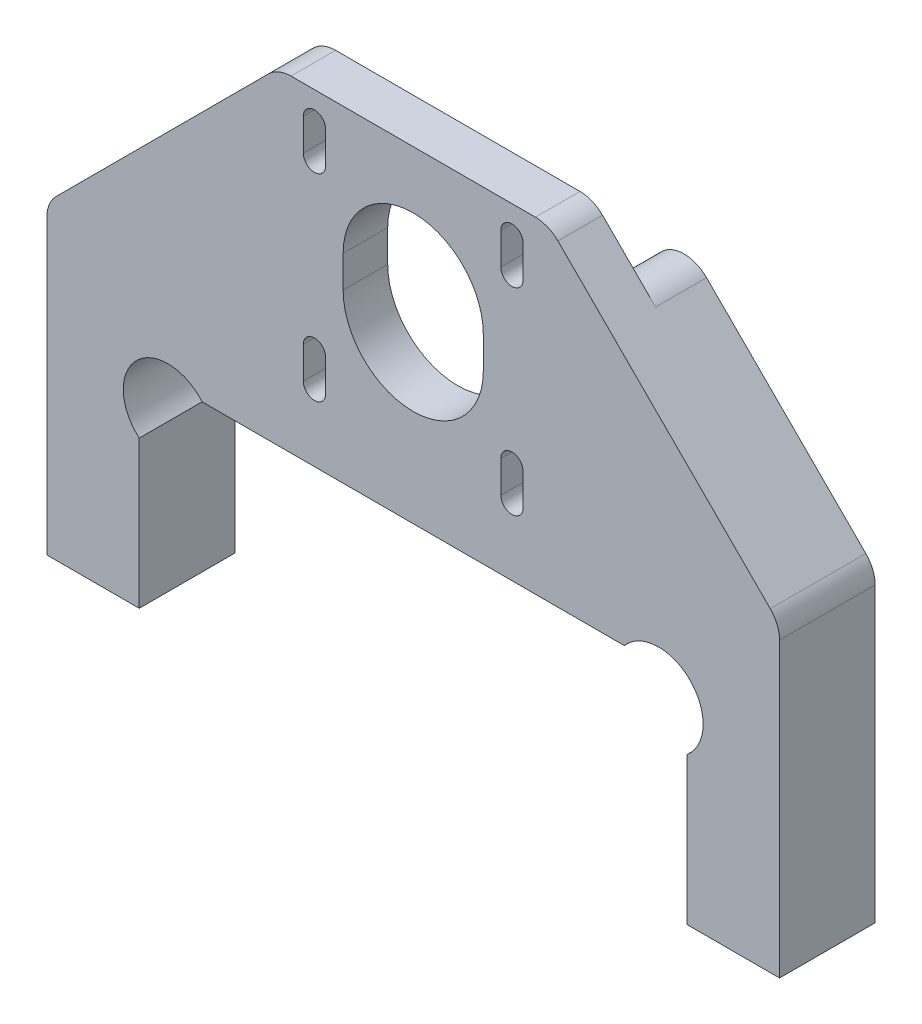
SolidWorks part; units mm, degrees
ref_plane "Ebene vorne" through (0, 0, 0) normal (0, 0, 1) x (1, 0, 0)
ref_plane "Ebene oben" through (0, 0, 0) normal (0, 1, 0) x (1, 0, 0)
ref_plane "Ebene rechts" through (0, 0, 0) normal (1, 0, 0) x (0, 0, -1)
sketch "Skizze1" plane through (0, 0, 0) normal (0, 0, 1) x (1, 0, 0)
  line L0 (100.5, 0) -> (115, 0)
  line L1 (0, 0) -> (14.5, 0)
  line L2 (0, 0) -> (0, 48)
  line L4 (115, 0) -> (115, 48)
  line L5 (0, 48) -> (36.25, 84.25)
  line L6 (14.5, 0) -> (14.5, 23.1381)
  line L7 (24.3619, 33) -> (90.6381, 33)
  line L8 (100.5, 0) -> (100.5, 23.1381)
  line L9 (36.25, 84.25) -> (78.75, 84.25)
  line L10 (78.75, 84.25) -> (115, 48)
  line L11 (57.5, 64.25) -> (57.5, 59.25) construction
  line L12 (68.5, 64.25) -> (68.5, 59.25)
  line L13 (46.5, 64.25) -> (46.5, 59.25)
  line L14 (42, 79.75) -> (42, 74.75) construction
  line L15 (43.75, 79.75) -> (43.75, 74.75)
  line L16 (40.25, 79.75) -> (40.25, 74.75)
  line L17 (73, 79.75) -> (73, 74.75) construction
  line L18 (74.75, 79.75) -> (74.75, 74.75)
  line L19 (71.25, 79.75) -> (71.25, 74.75)
  line L20 (73, 48.75) -> (73, 43.75) construction
  line L21 (74.75, 48.75) -> (74.75, 43.75)
  line L22 (71.25, 48.75) -> (71.25, 43.75)
  line L23 (42, 48.75) -> (42, 43.75) construction
  line L24 (43.75, 48.75) -> (43.75, 43.75)
  line L25 (40.25, 48.75) -> (40.25, 43.75)
  arc A0 (68.5, 64.25) -> (46.5, 64.25) centre (57.5, 64.25) ccw
  arc A1 (46.5, 59.25) -> (68.5, 59.25) centre (57.5, 59.25) ccw
  arc A2 (43.75, 79.75) -> (40.25, 79.75) centre (42, 79.75) ccw
  arc A3 (40.25, 74.75) -> (43.75, 74.75) centre (42, 74.75) ccw
  arc A4 (74.75, 79.75) -> (71.25, 79.75) centre (73, 79.75) ccw
  arc A5 (71.25, 74.75) -> (74.75, 74.75) centre (73, 74.75) ccw
  arc A6 (74.75, 48.75) -> (71.25, 48.75) centre (73, 48.75) ccw
  arc A7 (71.25, 43.75) -> (74.75, 43.75) centre (73, 43.75) ccw
  arc A8 (43.75, 48.75) -> (40.25, 48.75) centre (42, 48.75) ccw
  arc A9 (40.25, 43.75) -> (43.75, 43.75) centre (42, 43.75) ccw
  arc A10 (24.3619, 33) -> (14.5, 23.1381) centre (19, 28.5) ccw
  arc A11 (100.5, 23.1381) -> (90.6381, 33) centre (96, 28.5) ccw
  point P11 (57.5, 61.75)
  point P20 (42, 77.25)
  point P30 (73, 77.25)
  point P37 (73, 46.25)
  point P44 (42, 46.25)
  dimension "D7" = 61.75
  dimension "D20" = 14
  dimension "D21" = 14
  dimension "D23" = 4.5
  dimension "D24" = 4.5
  dimension "D3" = 42.5
  dimension "D4" = 14.5
  dimension "D5" = 115
  dimension "D6" = 36.25
  dimension "D8" = 45
  dimension "D9" = 45
  dimension "D10" = 22
  dimension "D11" = 5
  dimension "D12" = 22.5
  dimension "D13" = 21.25
  dimension "D14" = 3.5
  dimension "D15" = 5
  dimension "D16" = 15.5
  dimension "D17" = 15.5
  dimension "D22" = 4.5
  dimension "D25" = 4.5
  dimension "D18" = 2
  dimension "D19" = 2
extrude "Aufsatz-Linear austragen1" add sketch "Skizze1" along normal blind 15
hole_wizard "M5 Gewindebohrung1" positions "Skizze3" profile "Skizze2" tap size "M5" standard "DIN"
sketch "Skizze3" plane through (0, 0, 0) normal (0, -1, 0) x (-1, 0, 0)
  line L0 (0, -15) -> (0, 0) construction
  line L1 (0, -15) -> (-14.5, -15) construction
  line L2 (-115, -15) -> (-115, 0) construction
  line L3 (-100.5, -15) -> (-115, -15) construction
  point P0 (-7.5, -7.5)
  point P2 (-107.5, -7.5)
  point P16 (-107.75, -15)
  dimension "D1" = 7.5
  dimension "D2" = 7.5
  dimension "D3" = 7.5
  dimension "D4" = 7.5
sketch "Skizze2" plane through (7.5, 0, 7.5) normal (1, 0, 0) x (0, 0, -1)
  line L0 (0, 0) -> (0, 15.2618)
  line L1 (0, 15.2618) -> (2.1, 14)
  line L2 (2.1, 14) -> (2.1, 0)
  line L5 (2.1, 0) -> (0, 0)
  line L10 (0, 15.2618) -> (-2.1, 14) construction
  line L11 (0, -6.35) -> (0, 107.95) construction
  dimension "Bohrerdurchmesser" = 4.2
  dimension "Bohrungstiefe" = 14
  dimension "Spitzenwinkel" = 118
cosmetic thread "Bohrungsgewinde1" parameters "D1"=10, "D2"=5
cosmetic thread "Bohrungsgewinde2" parameters "D1"=10, "D2"=5
sketch "Skizze4" plane through (0, 0, 0) normal (0, 0, -1) x (-1, 0, 0)
  line L0 (-24.3619, 33) -> (-90.6381, 33) construction
  line L1 (-80, 33) -> (-35, 33)
  line L2 (-80, 33) -> (-80, 84.25)
  line L3 (-80, 84.25) -> (-35, 84.25)
  line L4 (-35, 33) -> (-35, 84.25)
  dimension "D1" = 45
  dimension "D2" = 1.25
extrude "Schnitt-Linear austragen1" cut sketch "Skizze4" against normal blind 8
fillet "Verrundung1" radius 5 2 edges at (35, 83, 4) (80, 83, 4)
fillet "Verrundung2" radius 5 4 edges at (0, 48, 7.5) (115, 48, 7.5) (36.25, 84.25, 11.5) (78.75, 84.25, 11.5)
hole_wizard "M3 Gewindebohrung1" positions "Skizze7" profile "Skizze6" tap size "M3" standard "DIN"
sketch "Skizze7" plane through (0, 0, 0) normal (0, 0, -1) x (-1, 0, 0)
  point P0 (-3.5, 37.7)
  point P3 (-22.5, 37.7)
sketch "Skizze6" plane through (3.5, 37.7, 0) normal (1, 0, 0) x (0, 1, 0)
  line L0 (0, 0) -> (0, 9.2511)
  line L1 (0, 9.2511) -> (1.25, 8.5)
  line L2 (1.25, 8.5) -> (1.25, 0)
  line L5 (1.25, 0) -> (0, 0)
  line L10 (0, 9.2511) -> (-1.25, 8.5) construction
  line L11 (0, -6.35) -> (0, 107.95) construction
  dimension "Bohrerdurchmesser" = 2.5
  dimension "Bohrungstiefe" = 8.5
  dimension "Spitzenwinkel" = 118
cosmetic thread "Bohrungsgewinde3" parameters "D1"=6, "D2"=3
cosmetic thread "Bohrungsgewinde4" parameters "D1"=6, "D2"=3
